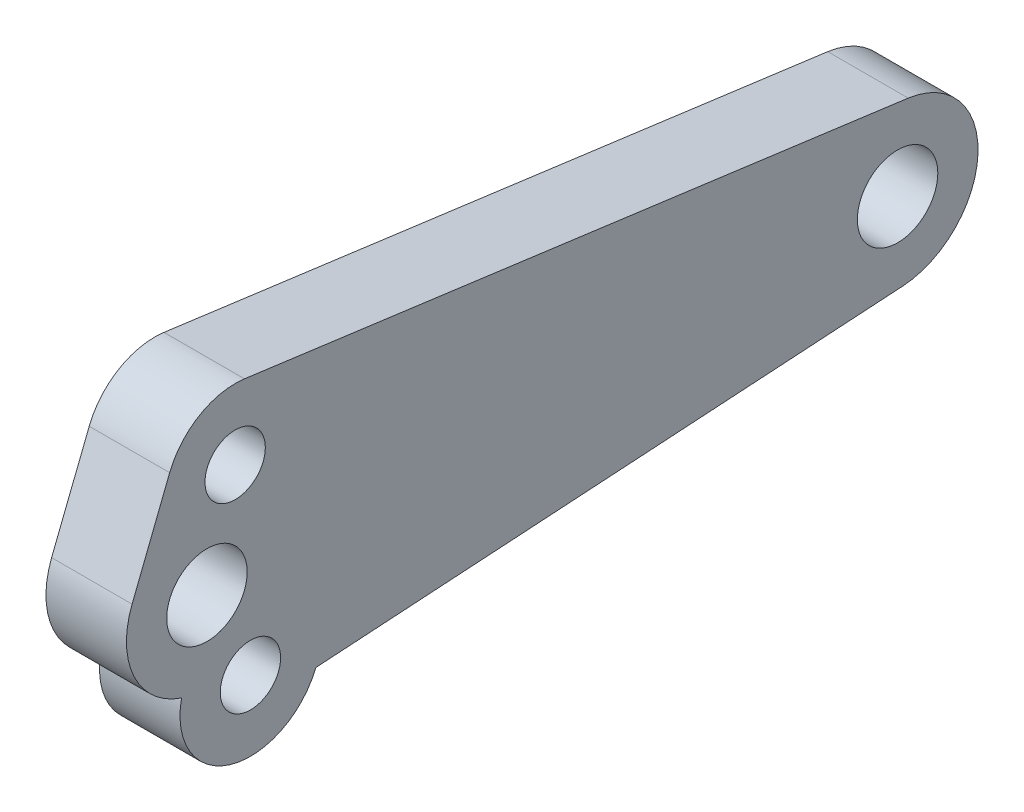
SolidWorks part; units mm, degrees
ref_plane "Front Plane" through (0, 0, 0) normal (0, 0, 1) x (1, 0, 0)
ref_plane "Top Plane" through (0, 0, 0) normal (0, 1, 0) x (1, 0, 0)
ref_plane "Right Plane" through (0, 0, 0) normal (1, 0, 0) x (0, 0, -1)
sketch "Sketch1" plane through (0, 0, 0) normal (1, 0, 0) x (0, 0, -1)
  line L0 (0, 0) -> (17.1622, 0) construction
  line L1 (2.706, -2.9114) -> (17.2875, -1.9961)
  line L2 (0.9333, 4.1878) -> (17.4273, 1.9824)
  line L3 (-0.926, 3.0968) -> (-1.8598, 0.7356)
  circle A0 centre (0, 0) radius 1
  circle A1 centre (17.1622, 0) radius 1
  circle A2 centre (0.7014, 2.4532) radius 0.75
  circle A3 centre (1.081, -2.2619) radius 0.75
  arc A4 (17.2875, -1.9961) -> (17.4273, 1.9824) centre (17.1622, 0) ccw
  arc A5 (0.9333, 4.1878) -> (-0.926, 3.0968) centre (0.7014, 2.4532) ccw
  arc A6 (-1.8598, 0.7356) -> (-0.6307, -1.8979) centre (0, 0) ccw
  arc A7 (-0.6307, -1.8979) -> (2.706, -2.9114) centre (1.081, -2.2619) ccw
  circle A8 centre (17.1622, 0) radius 2 construction
  circle A9 centre (0.7014, 2.4532) radius 1.75 construction
  circle A10 centre (0, 0) radius 2 construction
  circle A11 centre (1.081, -2.2619) radius 1.75 construction
  point P16 (0.7014, 2.4532)
  point P18 (1.081, -2.2619)
  dimension "D1" = 2
  dimension "D2" = 2
  dimension "D3" = 1.5
  dimension "D4" = 1.5
  dimension "D5" = 1
extrude "Boss-Extrude1" add sketch "Sketch1" along normal blind 2
